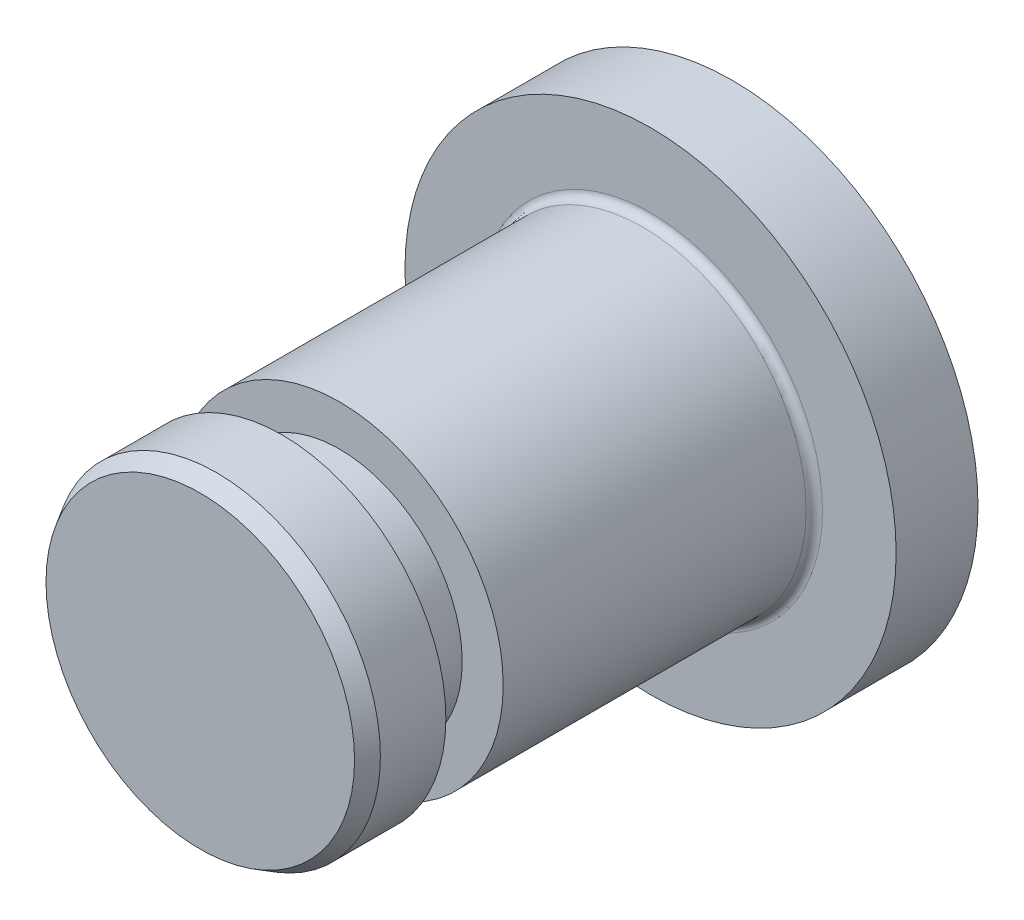
SolidWorks part; units mm, degrees
ref_plane "前视基准面" through (0, 0, 0) normal (0, 0, 1) x (1, 0, 0)
ref_plane "上视基准面" through (0, 0, 0) normal (0, 1, 0) x (1, 0, 0)
ref_plane "右视基准面" through (0, 0, 0) normal (1, 0, 0) x (0, 0, -1)
sketch "草图1" plane through (0, 0, 0) normal (0, 0, 1) x (1, 0, 0)
  circle A0 centre (0, 0) radius 30
  dimension "D1" = 60
extrude "凸台-拉伸1" add sketch "草图1" along normal blind 10
sketch "草图2" plane through (0, 0, 10) normal (0, 0, 1) x (1, 0, 0)
  circle A0 centre (0, 0) radius 20
  dimension "D1" = 40
extrude "凸台-拉伸2" add sketch "草图2" along normal blind 38
sketch "草图3" plane through (0, 0, 48) normal (0, 0, 1) x (1, 0, 0)
  circle A0 centre (0, 0) radius 15
  dimension "D1" = 30
extrude "凸台-拉伸3" add sketch "草图3" along normal blind 7
sketch "草图4" plane through (0, 0, 55) normal (0, 0, 1) x (1, 0, 0)
  circle A0 centre (0, 0) radius 20
  dimension "D1" = 40
extrude "凸台-拉伸4" add sketch "草图4" along normal blind 10
chamfer "倒角1" distance 2 angle 30 1 edges at (20, 0, 65)
fillet "圆角1" radius 1 1 edges at (20, 0, 10)
